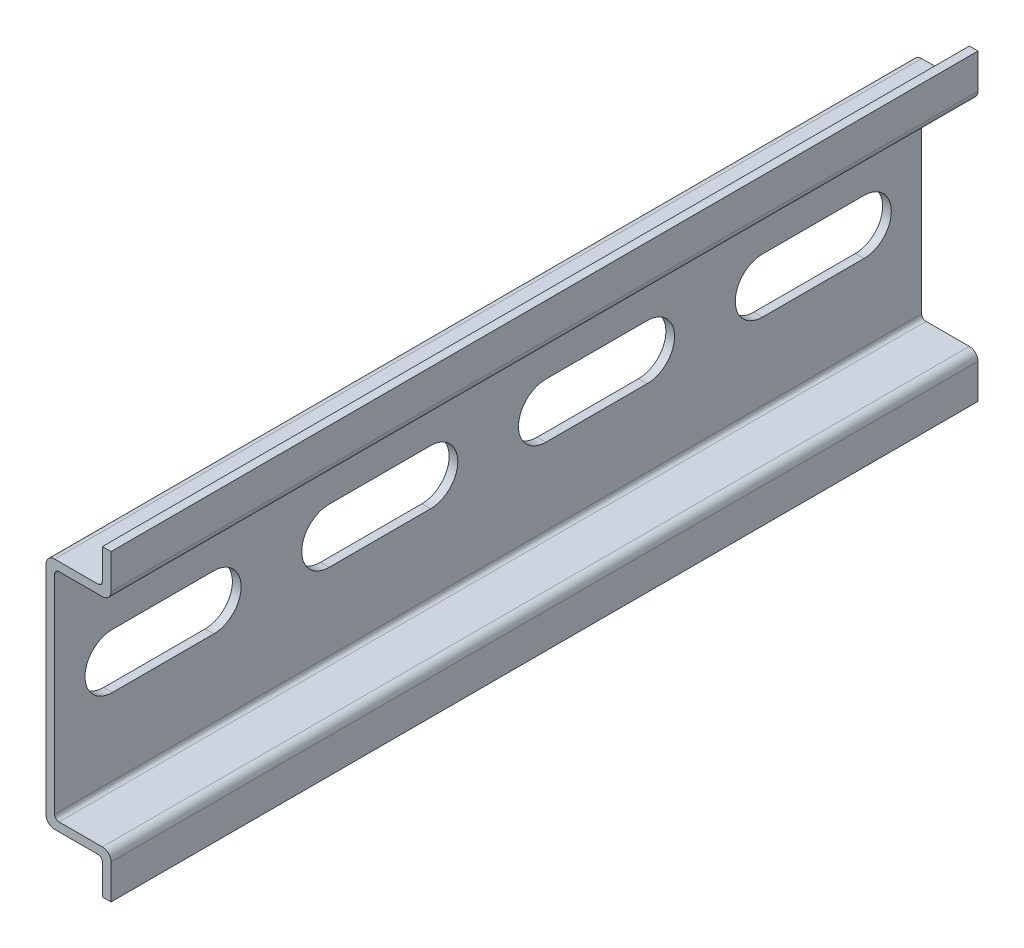
SolidWorks part; units mm, degrees
ref_plane "Front Plane" through (0, 0, 0) normal (0, 0, 1) x (1, 0, 0)
ref_plane "Top Plane" through (0, 0, 0) normal (0, 1, 0) x (1, 0, 0)
ref_plane "Right Plane" through (0, 0, 0) normal (1, 0, 0) x (0, 0, -1)
sketch "Sketch1" plane through (0, 0, 0) normal (0, 0, 1) x (1, 0, 0)
  line L0 (0, 0) -> (7.5, 0) construction
  line L1 (0, 17.5) -> (7.5, 17.5) construction
  line L2 (0, 17.5) -> (0, -17.5) construction
  line L3 (0, -17.5) -> (7.5, -17.5) construction
  line L4 (7.5, 17.5) -> (7.5, -17.5) construction
  line L5 (7.5, 17.5) -> (6.5, 17.5)
  line L6 (6.5, 17.5) -> (6.5, 14)
  line L7 (6, 13.5) -> (1, 13.5)
  line L8 (0, 12.5) -> (0, -12.5)
  line L9 (7.5, 17.5) -> (7.5, 13.5)
  line L10 (6.5, 12.5) -> (1.5, 12.5)
  line L11 (1, 12) -> (1, -12)
  line L12 (6.5, -12.5) -> (1.5, -12.5)
  line L13 (7.5, -17.5) -> (7.5, -13.5)
  line L14 (6, -13.5) -> (1, -13.5)
  line L15 (6.5, -17.5) -> (6.5, -14)
  line L16 (7.5, -17.5) -> (6.5, -17.5)
  line L17 (6.3536, 13.6464) -> (7.2071, 12.7929) construction
  line L18 (1.1464, 12.3536) -> (0.2929, 13.2071) construction
  arc A0 (1.5, 12.5) -> (1, 12) centre (1.5, 12) ccw
  arc A1 (1, 13.5) -> (0, 12.5) centre (1, 12.5) ccw
  arc A2 (7.5, 13.5) -> (6.5, 12.5) centre (6.5, 13.5) cw
  arc A3 (6, 13.5) -> (6.5, 14) centre (6, 14) ccw
  arc A4 (1, -13.5) -> (0, -12.5) centre (1, -12.5) cw
  arc A5 (1.5, -12.5) -> (1, -12) centre (1.5, -12) cw
  arc A6 (7.5, -13.5) -> (6.5, -12.5) centre (6.5, -13.5) ccw
  arc A7 (6, -13.5) -> (6.5, -14) centre (6, -14) cw
  dimension "D5" = 1
  dimension "D6" = 0.5
  dimension "D1" = 35
  dimension "D2" = 7.5
  dimension "D3" = 1
  dimension "D4" = 27
extrude "Boss-Extrude1" add sketch "Sketch1" along normal mid plane 100
sketch "Sketch2" plane through (0, 0, 0) normal (1, 0, 0) x (0, 0, -1)
  line L0 (-43.35, 0) -> (-31.65, 0) construction
  line L1 (-43.35, 3.15) -> (-31.65, 3.15)
  line L2 (-43.35, -3.15) -> (-31.65, -3.15)
  line L3 (-37.5, 0) -> (-50, 0) construction
  line L4 (-50, 12.5) -> (-50, -12.5) construction
  line L5 (-37.5, 0) -> (-12.5, 0) construction
  line L6 (-12.5, 0) -> (12.5, 0) construction
  arc A0 (-43.35, 3.15) -> (-43.35, -3.15) centre (-43.35, 0) ccw
  arc A1 (-31.65, -3.15) -> (-31.65, 3.15) centre (-31.65, 0) ccw
  point P2 (-37.5, 0)
  dimension "D1" = 6.3
  dimension "D2" = 18
  dimension "D4" = 12.5
  dimension "D3" = 25
extrude "Cut-Extrude1" cut sketch "Sketch2" along normal up to vertex (7.5 mm away) up to point (7.5, 0, 0)
pattern_linear "LPattern1" count 4 spacing 25 along (0, 0, -1) of "Cut-Extrude1"
equation "\"D4@Sketch2\" = \"D3@Sketch2\" / 2"
equation "\"D3@LPattern1\" = \"D3@Sketch2\""
equation "\"D1@LPattern1\" = \"D1@Boss-Extrude1\" / \"D3@LPattern1\""
